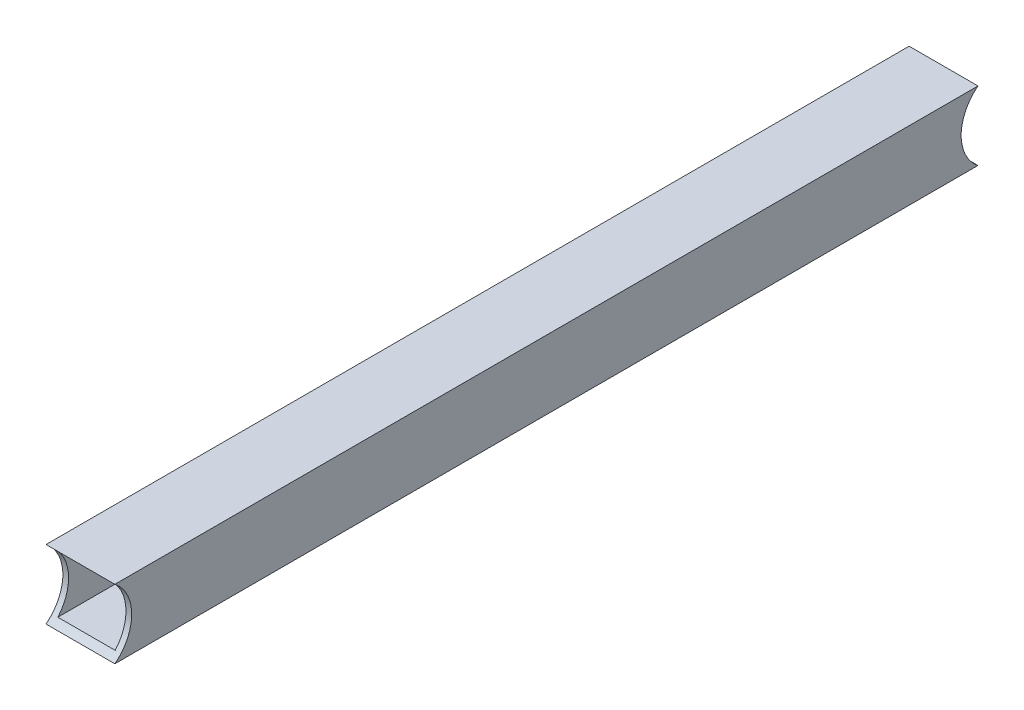
SolidWorks part; units mm, degrees
material "6063-T5"
ref_plane "Front Plane" through (0, 0, 0) normal (0, 0, 1) x (1, 0, 0)
ref_plane "Top Plane" through (0, 0, 0) normal (0, 1, 0) x (1, 0, 0)
ref_plane "Right Plane" through (0, 0, 0) normal (1, 0, 0) x (0, 0, -1)
sketch "Sketch1" plane through (0, 0, 0) normal (1, 0, 0) x (0, 0, -1)
  line L1 (0, 0) -> (507.1339, 0)
  line L2 (0, 0) -> (0, 38.1)
  line L3 (0, 38.1) -> (507.1339, 38.1)
  line L4 (507.1339, 0) -> (507.1339, 38.1)
  circle A0 centre (0, 19.05) radius 24.13
  circle A1 centre (507.1339, 19.05) radius 24.13
  dimension "D3" = 48.26
  dimension "D1" = 507.1339
  dimension "D2" = 38.1
extrude "Boss-Extrude1" add sketch "Sketch1" along normal blind 38.1 contours A1 L3 A0 L1
sketch "Sketch3" plane through (0, 0, 0) normal (0, 0, 1) x (1, 0, 0)
  line L0 (3.175, 34.925) -> (3.175, 3.175)
  line L1 (3.175, 3.175) -> (34.925, 3.175)
  line L2 (34.925, 3.175) -> (34.925, 34.925)
  line L3 (34.925, 34.925) -> (3.175, 34.925)
  line L4 (0, 38.1) -> (0, 0)
  line L5 (0, 0) -> (38.1, 0)
  line L6 (38.1, 0) -> (38.1, 38.1)
  line L7 (38.1, 38.1) -> (0, 38.1)
  line L8 (0, 38.1) -> (0, 0) construction
  line L9 (0, 0) -> (38.1, 0) construction
  line L10 (38.1, 0) -> (38.1, 38.1) construction
  line L11 (38.1, 38.1) -> (0, 38.1) construction
  dimension "D1" = 0
  dimension "D2" = 3.175
extrude "Cut-Extrude1" cut sketch "Sketch3" against normal through all
